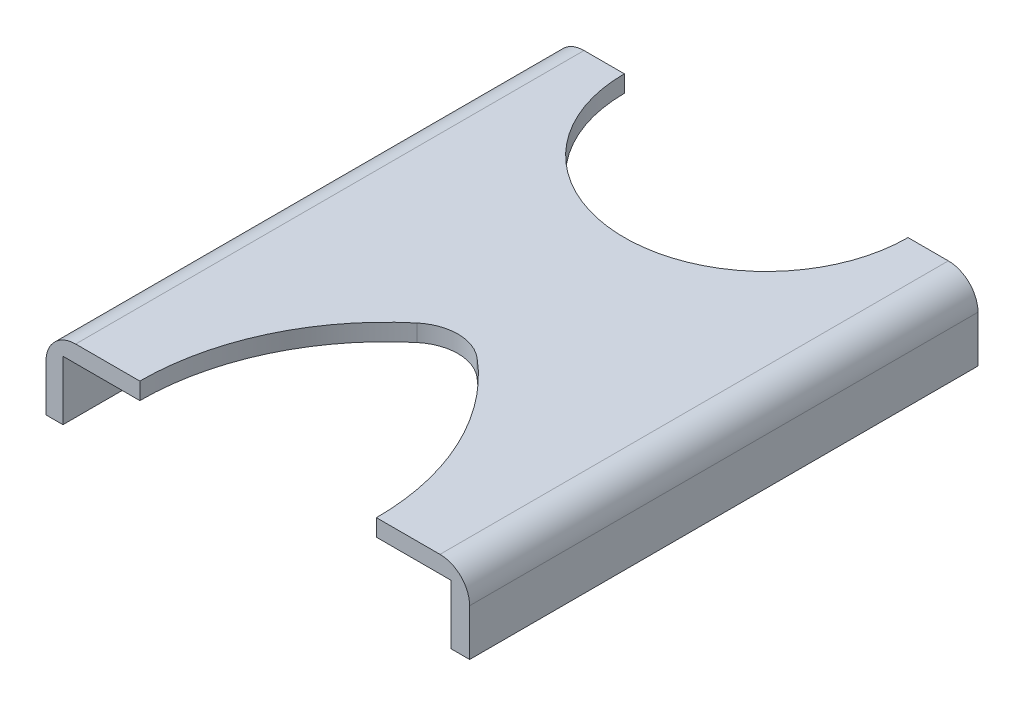
SolidWorks part; units mm, degrees
ref_plane "Front Plane" through (0, 0, 0) normal (0, 0, 1) x (1, 0, 0)
ref_plane "Top Plane" through (0, 0, 0) normal (0, 1, 0) x (1, 0, 0)
ref_plane "Right Plane" through (0, 0, 0) normal (1, 0, 0) x (0, 0, -1)
sketch "Sketch1" plane through (0, 0, 0) normal (0, 1, 0) x (1, 0, 0)
  line L1 (0, 0) -> (1000, 0)
  line L2 (0, 0) -> (0, 1200)
  line L3 (0, 1200) -> (1000, 1200)
  line L4 (1000, 0) -> (1000, 1200)
  dimension "D1" = 1000
  dimension "D2" = 1200
extrude "Boss-Extrude1" add sketch "Sketch1" along normal blind 40
sketch "Sketch2" plane through (0, 0, 0) normal (0, -1, 0) x (1, 0, 0)
  line L0 (1000, -1200) -> (0, -1200) construction
  line L1 (1000, 0) -> (955.8997, 0)
  line L2 (1000, 0) -> (1000, -1200)
  line L3 (1000, -1200) -> (955.8997, -1200)
  line L4 (955.8997, 0) -> (955.8997, -1200)
  line L6 (0, 0) -> (40, 0)
  line L7 (0, 0) -> (0, -1200)
  line L8 (0, -1200) -> (40, -1200)
  line L9 (40, 0) -> (40, -1200)
  dimension "D1" = 40
  dimension "D2" = 44.1003
extrude "Boss-Extrude2" add sketch "Sketch2" along normal blind 140
fillet "Fillet1" radius 70 2 edges at (1000, 40, -600) (0, 40, -600)
sketch "Sketch3" plane through (0, 40, 0) normal (0, 1, 0) x (1, 0, 0)
  line L0 (930, 1200) -> (70, 1200) construction
  line L1 (221.4411, 0) -> (780, 0)
  line L2 (70, 0) -> (930, 0) construction
  circle A0 centre (500, 1200) radius 334.8026
  arc A1 (221.4411, 0) -> (429.8671, 445.8992) centre (802.6244, 0) cw
  arc A2 (780, 0) -> (571.5739, 445.8992) centre (198.8166, 0) ccw
  arc A3 (429.8671, 445.8992) -> (571.5739, 445.8992) centre (500.7205, 361.1431) cw
  dimension "D1" = 151.4411
  dimension "D2" = 150
extrude "Cut-Extrude2" cut sketch "Sketch3" against normal blind 140 contours A0 | A3 A2 L1 A1
